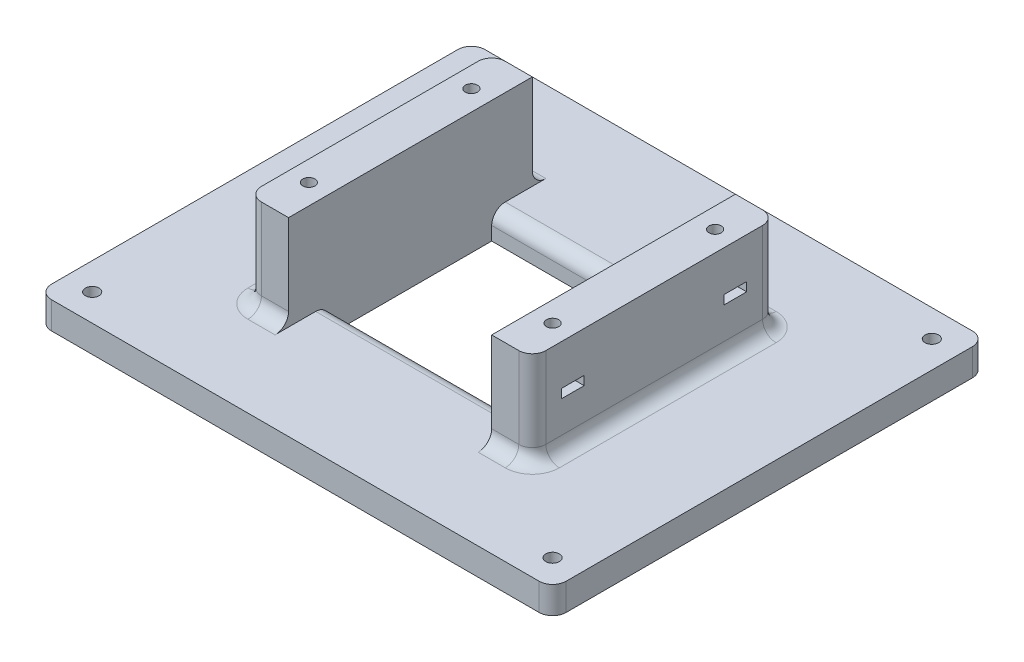
SolidWorks part; units mm, degrees
ref_plane "Front Plane" through (0, 0, 0) normal (0, 0, 1) x (1, 0, 0)
ref_plane "Top Plane" through (0, 0, 0) normal (0, 1, 0) x (1, 0, 0)
ref_plane "Right Plane" through (0, 0, 0) normal (1, 0, 0) x (0, 0, -1)
sketch "Sketch1" plane through (0, 0, 0) normal (0, 1, 0) x (1, 0, 0)
  line L9 (0, 0) -> (190, 0)
  line L10 (0, 0) -> (0, 160)
  line L11 (0, 160) -> (190, 160)
  line L12 (190, 0) -> (190, 160)
  dimension "D1" = 190
  dimension "D2" = 160
extrude "Boss-Extrude1" add sketch "Sketch1" along normal blind 10
sketch "Sketch3" plane through (0, 10, 0) normal (0, 1, 0) x (1, 0, 0)
  line L1 (42.5, 35) -> (57.5, 35)
  line L2 (42.5, 35) -> (42.5, 125)
  line L3 (42.5, 125) -> (57.5, 125)
  line L4 (57.5, 35) -> (57.5, 125)
  line L5 (42.5, 35) -> (57.5, 125) construction
  line L6 (42.5, 125) -> (57.5, 35) construction
  line L7 (0, 80) -> (190, 80) construction
  line L8 (0, 160) -> (0, 0) construction
  line L9 (190, 0) -> (190, 160) construction
  line L10 (95, 160) -> (95, 0) construction
  line L11 (190, 160) -> (0, 160) construction
  line L12 (0, 0) -> (190, 0) construction
  line L13 (147.5, 125) -> (132.5, 125)
  line L14 (132.5, 35) -> (132.5, 125)
  line L15 (147.5, 35) -> (132.5, 35)
  line L16 (147.5, 35) -> (147.5, 125)
  line L17 (132.5, 125) -> (147.5, 35) construction
  line L18 (147.5, 125) -> (132.5, 35) construction
  point P0 (50, 80)
  dimension "D1" = 45
  dimension "D2" = 75
  dimension "D3" = 90
extrude "Boss-Extrude3" add sketch "Sketch3" along normal blind 35
sketch "Sketch4" plane through (0, 45, 0) normal (0, 1, 0) x (1, 0, 0)
  line L0 (42.5, 80) -> (147.5, 80) construction
  line L1 (42.5, 125) -> (42.5, 35) construction
  line L2 (147.5, 35) -> (147.5, 125) construction
  line L3 (50, 110) -> (50, 80) construction
  line L4 (50, 125) -> (50, 110) construction
  line L5 (57.5, 125) -> (42.5, 125) construction
  circle A0 centre (50, 110) radius 2.25
  circle A1 centre (140, 110) radius 2.25
  circle A2 centre (140, 50) radius 2.25
  circle A3 centre (50, 50) radius 2.25
  dimension "D1" = 4.5
  dimension "D4" = 30
  dimension "D2" = 2
  dimension "D3" = 2
extrude "Cut-Extrude1" cut sketch "Sketch4" against normal blind 50
sketch "Sketch5" plane through (0, 10, 0) normal (0, 1, 0) x (1, 0, 0)
  line L0 (57.5, 35) -> (57.5, 125) construction
  line L1 (57.5, 110) -> (132.5, 110)
  line L2 (57.5, 110) -> (57.5, 50)
  line L3 (57.5, 50) -> (132.5, 50)
  line L4 (132.5, 110) -> (132.5, 50)
  line L5 (132.5, 125) -> (132.5, 35) construction
  line L6 (57.5, 35) -> (57.5, 125) construction
  line L7 (52.25, 110) -> (57.5, 110) construction
  line L8 (50, 50) -> (57.5, 50) construction
  circle A3 centre (50, 110) radius 2.25 construction
extrude "Cut-Extrude2" cut sketch "Sketch5" against normal blind 50
sketch "Sketch6" plane through (0, 0, 0) normal (0, -1, 0) x (-1, 0, 0)
  circle A0 centre (-50, 50) radius 4.5
  circle A1 centre (-140, 50) radius 4.5
  circle A2 centre (-140, 110) radius 4.5
  circle A3 centre (-50, 110) radius 4.5
  dimension "D1" = 2
  dimension "D2" = 2
extrude "Cut-Extrude3" [suppressed] cut sketch "Sketch6" against normal blind 10
sketch "Sketch8" plane through (0, 10, 0) normal (0, 1, 0) x (1, 0, 0)
  line L0 (10, 150) -> (10, 160) construction
  line L1 (190, 160) -> (0, 160) construction
  line L2 (10, 150) -> (0, 150) construction
  line L3 (0, 160) -> (0, 0) construction
  line L4 (190, 0) -> (190, 160) construction
  line L5 (0, 0) -> (190, 0) construction
  circle A0 centre (10, 150) radius 2.5
  circle A1 centre (180, 150) radius 2.5
  circle A2 centre (180, 10) radius 2.5
  circle A3 centre (10, 10) radius 2.5
  dimension "D1" = 10
  dimension "D2" = 10
  dimension "D5" = 10
  dimension "D6" = 10
  dimension "D3" = 2
  dimension "D4" = 2
extrude "Cut-Extrude4" cut sketch "Sketch8" against normal blind 10 contours A0
fillet "Fillet1" radius 5 14 edges at (147.5, 27.5, -35) (147.5, 27.5, -125) (42.5, 27.5, -35) (42.5, 27.5, -125) (50, 10, -125) (140, 10, -125) (140, 10, -35) (50, 10, -35) (42.5, 10, -80) (147.5, 10, -80) (190, 5, -160) (190, 5, 0) (0, 5, -160) (0, 5, 0)
fillet "Fillet2" radius 5 2 edges at (95, 10, -50) (95, 10, -110)
ref_plane "Plane1" through (0, 30, 0) normal (0, 1, 0) x (1, 0, 0)
sketch "Sketch10" plane through (0, 30, 0) normal (0, 1, 0) x (1, 0, 0)
  line L0 (45.8514, 54.1486) -> (42.5, 54.1486)
  line L1 (54.1514, 45.8486) -> (45.8459, 45.8486)
  line L2 (54.1514, 45.8486) -> (54.1514, 54.1486)
  line L3 (54.1514, 54.1486) -> (45.8514, 54.1486)
  line L5 (54.1514, 45.8486) -> (45.8514, 54.1486) construction
  line L6 (54.1514, 54.1486) -> (45.8459, 45.8486) construction
  line L7 (42.5, 120) -> (42.5, 40) construction
  line L8 (42.5, 54.1486) -> (42.5, 45.8486)
  line L9 (42.5, 45.8486) -> (45.8459, 45.8486)
  line L10 (42.5, 105.8486) -> (45.8459, 105.8486)
  line L11 (54.1514, 105.8486) -> (45.8459, 105.8486)
  line L12 (54.1514, 105.8486) -> (54.1514, 114.1486)
  line L13 (54.1514, 114.1486) -> (45.8514, 114.1486)
  line L14 (45.8514, 114.1486) -> (42.5, 114.1486)
  line L15 (42.5, 114.1486) -> (42.5, 105.8486)
  line L16 (57.5, 125) -> (132.5, 125) construction
  line L17 (57.5, 125) -> (47.5, 125) construction
  line L18 (57.5, 125) -> (47.5, 125) construction
  line L19 (95, 125) -> (95, 29.9699) construction
  line L20 (135.8486, 54.1486) -> (144.1541, 45.8486) construction
  line L21 (135.8486, 45.8486) -> (144.1486, 54.1486) construction
  line L22 (147.5, 45.8486) -> (144.1541, 45.8486)
  line L23 (147.5, 54.1486) -> (147.5, 45.8486)
  line L24 (135.8486, 54.1486) -> (144.1486, 54.1486)
  line L25 (135.8486, 45.8486) -> (135.8486, 54.1486)
  line L26 (135.8486, 45.8486) -> (144.1541, 45.8486)
  line L27 (144.1486, 54.1486) -> (147.5, 54.1486)
  line L28 (147.5, 114.1486) -> (147.5, 105.8486)
  line L29 (144.1486, 114.1486) -> (147.5, 114.1486)
  line L30 (135.8486, 114.1486) -> (144.1486, 114.1486)
  line L31 (135.8486, 105.8486) -> (135.8486, 114.1486)
  line L32 (135.8486, 105.8486) -> (144.1541, 105.8486)
  line L33 (147.5, 105.8486) -> (144.1541, 105.8486)
  point P0 (50, 50)
  point P25 (0, 0)
  point P32 (140, 50)
  dimension "D1" = 8.3
  dimension "D2" = 8.3
  dimension "D3" = 2
extrude "Cut-Extrude5" cut sketch "Sketch10" against normal blind 3.3
